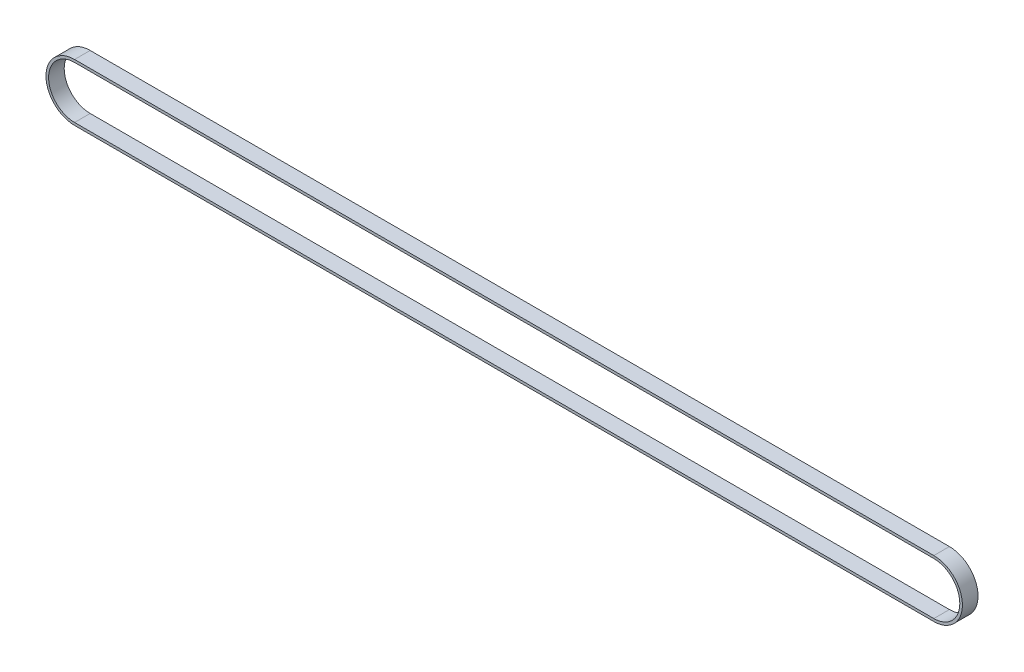
SolidWorks part; units mm, degrees
ref_plane "Front Plane" through (0, 0, 0) normal (0, 0, 1) x (1, 0, 0)
ref_plane "Top Plane" through (0, 0, 0) normal (0, 1, 0) x (1, 0, 0)
ref_plane "Right Plane" through (0, 0, 0) normal (1, 0, 0) x (0, 0, -1)
sketch "Sketch1" plane through (0, 0, 0) normal (0, 0, 1) x (1, 0, 0)
  line L0 (0, 0) -> (330.7, 0) construction
  line L1 (0, 10) -> (330.7, 10)
  line L2 (0, -10) -> (330.7, -10)
  line L3 (0, 11) -> (330.7, 11)
  line L4 (0, -11) -> (330.7, -11)
  arc A0 (0, 10) -> (0, -10) centre (0, 0) ccw
  arc A1 (330.7, -10) -> (330.7, 10) centre (330.7, 0) ccw
  arc A2 (330.7, -11) -> (330.7, 11) centre (330.7, 0) ccw
  arc A3 (0, 11) -> (0, -11) centre (0, 0) ccw
  point P3 (165.35, 0)
  dimension "D1" = 10
  dimension "D2" = 330.7
  dimension "D3" = 1
extrude "Boss-Extrude1" add sketch "Sketch1" along normal blind 6
